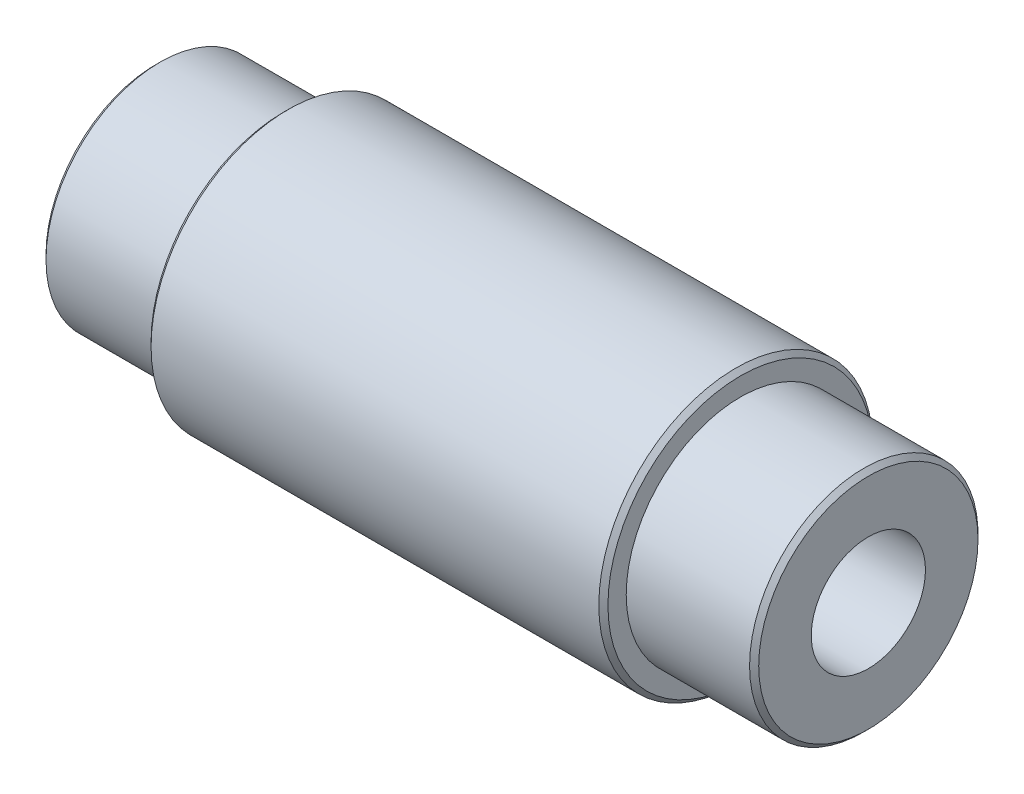
SolidWorks part; units mm, degrees
material "45"
ref_plane "前视基准面" through (0, 0, 0) normal (0, 0, 1) x (1, 0, 0)
ref_plane "上视基准面" through (0, 0, 0) normal (0, 1, 0) x (1, 0, 0)
ref_plane "右视基准面" through (0, 0, 0) normal (1, 0, 0) x (0, 0, -1)
sketch "草图2" plane through (0, 0, 0) normal (0, 0, 1) x (1, 0, 0)
  line L0 (-7.8, 0) -> (8.6023, 0) construction
  line L1 (-7.8, 0) -> (-7.8, 2.5)
  line L2 (-7.8, 2.5) -> (-5, 2.5)
  line L3 (-5, 2.5) -> (-5, 3)
  line L4 (-5, 3) -> (5, 3)
  line L5 (5, 3) -> (5, 2.5)
  line L6 (5, 2.5) -> (7.8, 2.5)
  line L7 (7.8, 2.5) -> (7.8, 0)
  line L8 (7.8, 0) -> (-7.8, 0)
  line L9 (0, 0) -> (0, 3) construction
  dimension "D1" = 6
  dimension "D2" = 5
  dimension "D3" = 2.8
  dimension "D4" = 10
revolve "旋转1" add sketch "草图2" angle 360 about L0
hole_wizard "M3 螺纹孔2" positions "草图6" profile "草图5" tap size "M3" standard "Gb"
sketch "草图6" plane through (-7.8, 0, 0) normal (-1, 0, 0) x (0, 0, 1)
  circle A0 centre (0, 0) radius 2.5 construction
  point P0 (0, 0)
sketch "草图5" plane through (-7.8, 0, 0) normal (0, 1, 0) x (0, 0, 1)
  line L0 (0, 0) -> (0, 6.7511)
  line L1 (0, 6.7511) -> (1.25, 6)
  line L2 (1.25, 6) -> (1.25, 0)
  line L5 (1.25, 0) -> (0, 0)
  line L10 (0, 6.7511) -> (-1.25, 6) construction
  line L11 (0, -6.35) -> (0, 107.95) construction
  dimension "螺纹孔钻头直径" = 2.5
  dimension "螺纹孔钻头深度" = 6
  dimension "导头角度" = 118
cosmetic thread "孔螺蚊线2" parameters "D1"=4, "D2"=3
hole_wizard "M3 螺纹孔3" positions "草图8" profile "草图7" tap size "M3" standard "Gb"
sketch "草图8" plane through (7.8, 0, 0) normal (1, 0, 0) x (0, 0, -1)
  circle A0 centre (0, 0) radius 2.5 construction
  point P0 (0, 0)
sketch "草图7" plane through (7.8, 0, 0) normal (0, 1, 0) x (0, 0, -1)
  line L0 (0, 0) -> (0, 7.2511)
  line L1 (0, 7.2511) -> (1.25, 6.5)
  line L2 (1.25, 6.5) -> (1.25, 0)
  line L5 (1.25, 0) -> (0, 0)
  line L10 (0, 7.2511) -> (-1.25, 6.5) construction
  line L11 (0, -6.35) -> (0, 107.95) construction
  dimension "螺纹孔钻头直径" = 2.5
  dimension "螺纹孔钻头深度" = 6.5
  dimension "导头角度" = 118
cosmetic thread "孔螺蚊线3" parameters "D1"=4, "D2"=3
chamfer "倒角1" distance 0.1 angle 45 4 edges at (7.8, 0, 2.5) (5, 0, 3) (-5, 0, 3) (-7.8, 0, 2.5)
